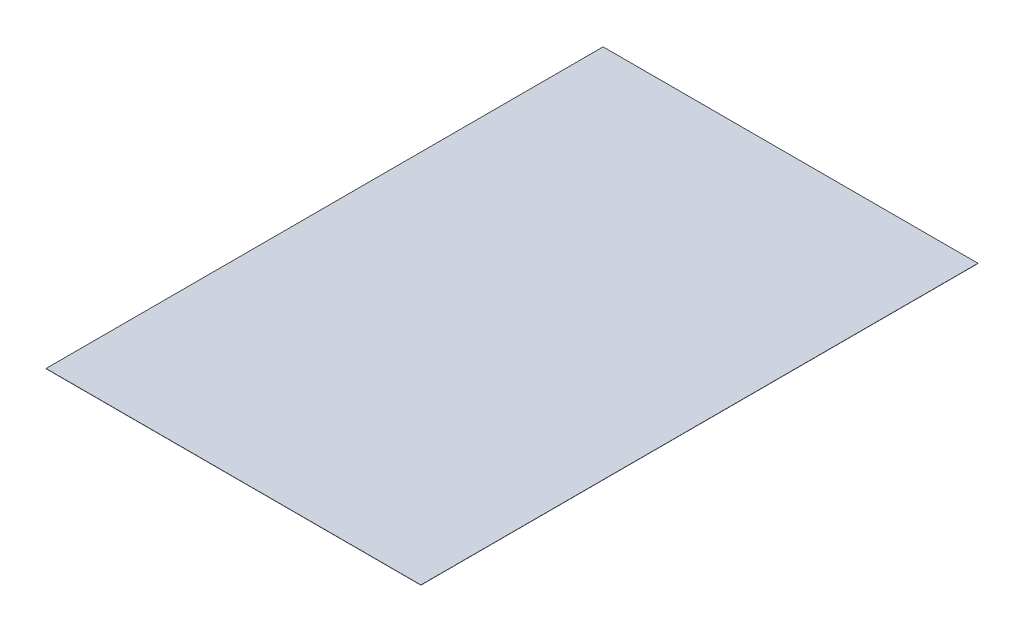
SolidWorks part; units mm, degrees
ref_plane "Спереди" through (0, 0, 0) normal (0, 0, 1) x (1, 0, 0)
ref_plane "Сверху" through (0, 0, 0) normal (0, 1, 0) x (1, 0, 0)
ref_plane "Справа" through (0, 0, 0) normal (1, 0, 0) x (0, 0, -1)
other "Configuration Table"
sketch "Эскиз1" plane through (0, 0, 0) normal (0, 1, 0) x (1, 0, 0)
  line L1 (1043, 1550) -> (-1043, 1550)
  line L2 (1043, 1550) -> (1043, -1550)
  line L3 (1043, -1550) -> (-1043, -1550)
  line L4 (-1043, 1550) -> (-1043, -1550)
  line L5 (1043, 1550) -> (-1043, -1550) construction
  line L6 (1043, -1550) -> (-1043, 1550) construction
  point P0 (0, 0)
extrude "Бобышка-Вытянуть1" add sketch "Эскиз1" along normal blind 1
